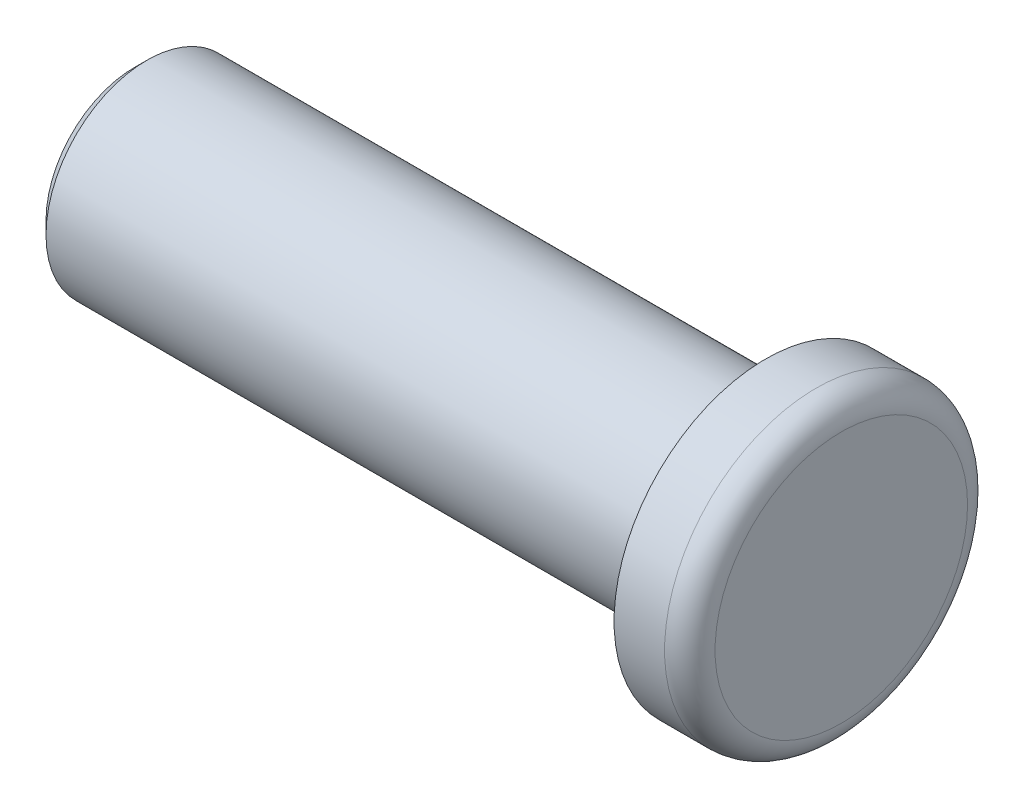
SolidWorks part; units mm, degrees
ref_plane "Front Plane" through (0, 0, 0) normal (0, 0, 1) x (1, 0, 0)
ref_plane "Top Plane" through (0, 0, 0) normal (0, 1, 0) x (1, 0, 0)
ref_plane "Right Plane" through (0, 0, 0) normal (1, 0, 0) x (0, 0, -1)
sketch "Sketch1" plane through (0, 0, 0) normal (1, 0, 0) x (0, 0, -1)
  circle A0 centre (0, 0) radius 6
  circle A1 centre (0, 0) radius 4
  dimension "D1" = 12
  dimension "D2" = 8
extrude "Boss-Extrude1" add sketch "Sketch1" along normal blind 3 contours A0
sketch "Sketch3" plane through (0, 0, 0) normal (-1, 0, 0) x (0, 0, 1)
  circle A0 centre (0, 0) radius 4
extrude "Boss-Extrude2" add sketch "Sketch3" along normal blind 25
fillet "Fillet1" radius 1 1 edges at (3, 0, -6)
chamfer "Chamfer1" distance 0.5 angle 45 1 edges at (-25, 0, 4)
